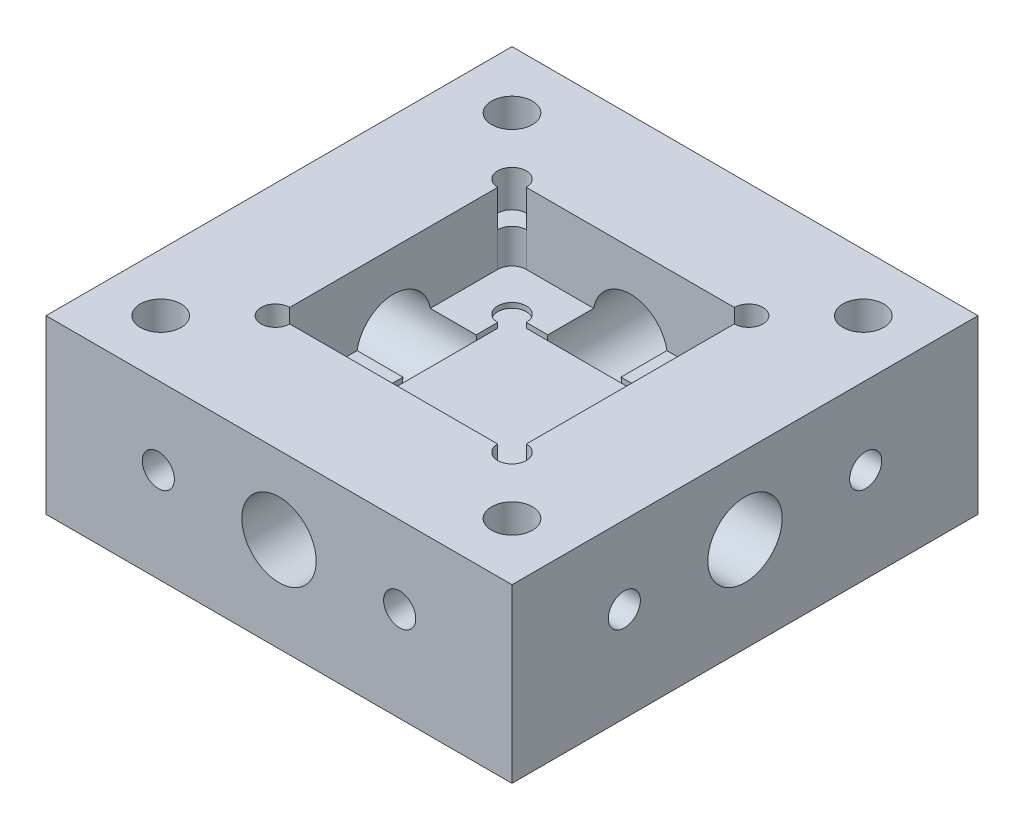
SolidWorks part; units mm, degrees
ref_plane "Front Plane" through (0, 0, 0) normal (0, 0, 1) x (1, 0, 0)
ref_plane "Top Plane" through (0, 0, 0) normal (0, 1, 0) x (1, 0, 0)
ref_plane "Right Plane" through (0, 0, 0) normal (1, 0, 0) x (0, 0, -1)
sketch "Sketch1" plane through (0, 0, 0) normal (0, 1, 0) x (1, 0, 0)
  line L1 (-12.9, -12.9) -> (12.9, -12.9)
  line L2 (-12.9, -12.9) -> (-12.9, 12.9)
  line L3 (-12.9, 12.9) -> (12.9, 12.9)
  line L4 (12.9, -12.9) -> (12.9, 12.9)
  line L5 (-12.9, -12.9) -> (12.9, 12.9) construction
  line L6 (-12.9, 12.9) -> (12.9, -12.9) construction
  point P0 (0, 0)
  dimension "D1" = 25.8
  dimension "D2" = 25.8
extrude "Boss-Extrude1" add sketch "Sketch1" along normal blind 9.525
sketch "Sketch3" plane through (-12.9, 0, 0) normal (-1, 0, 0) x (0, 0, 1)
  circle A0 centre (0, 5.2324) radius 2.0574
  dimension "D1" = 4.1148
extrude "Cut-Extrude3" cut sketch "Sketch3" against normal blind 8.89
mirror "Mirror1" about plane through (0, 0, 0) normal (1, 0, 0) of "Cut-Extrude3"
sketch "Sketch7" plane through (0, 0, -12.9) normal (0, 0, -1) x (-1, 0, 0)
  circle A0 centre (0, 5.2324) radius 2.0574
  dimension "D1" = 4.1148
extrude "Cut-Extrude5" cut sketch "Sketch7" against normal blind 8.89
mirror "Mirror2" about plane through (0, 0, 0) normal (0, 0, 1) of "Cut-Extrude5"
sketch "Sketch8" plane through (12.9, 0, 0) normal (1, 0, 0) x (0, 0, -1)
  point P3 (6.6802, 5.2324)
sketch "Sketch12" plane through (0, 9.525, 0) normal (0, 1, 0) x (1, 0, 0)
  line L10 (9.725, -9.725) -> (9.725, 9.725)
  line L11 (9.725, 9.725) -> (-9.725, 9.725)
  line L12 (-9.725, 9.725) -> (-9.725, -9.725)
  line L14 (-9.725, -9.725) -> (9.725, -9.725)
  line L15 (9.725, -9.725) -> (9.725, 9.725)
  line L16 (9.725, 9.725) -> (-9.725, 9.725)
  line L17 (-9.725, 9.725) -> (-9.725, -9.725)
  line L18 (-9.725, -9.725) -> (9.725, -9.725)
  dimension "D1" = 3.175
sketch "Sketch14" plane through (0, 9.525, 0) normal (0, 1, 0) x (1, 0, 0)
  line L1 (-5.7562, -6.55) -> (5.7562, -6.55)
  line L2 (-6.55, -5.7562) -> (-6.55, 5.7562)
  line L3 (-5.7562, 6.55) -> (5.7562, 6.55)
  line L4 (6.55, -5.7562) -> (6.55, 5.7562)
  line L5 (-6.55, -6.55) -> (6.55, 6.55) construction
  line L6 (-6.55, 6.55) -> (6.55, -6.55) construction
  arc A0 (5.7562, -6.55) -> (6.55, -5.7562) centre (5.7562, -5.7562) ccw
  arc A1 (-6.55, -5.7562) -> (-5.7562, -6.55) centre (-5.7562, -5.7562) ccw
  arc A2 (6.55, 5.7562) -> (5.7562, 6.55) centre (5.7562, 5.7562) ccw
  arc A3 (-6.55, 5.7562) -> (-5.7562, 6.55) centre (-5.7562, 5.7562) cw
  point P0 (0, 0)
  dimension "D3" = 0.7937
  dimension "D1" = 13.1
  dimension "D2" = 13.1
extrude "Cut-Extrude10" cut sketch "Sketch14" against normal blind 3.9376
sketch "Sketch15" plane through (0, 5.5874, 0) normal (0, 1, 0) x (1, 0, 0)
  line L1 (-3.2162, -4.01) -> (3.2162, -4.01)
  line L2 (-4.01, -3.2162) -> (-4.01, 3.2162)
  line L3 (-3.2163, 4.01) -> (3.2162, 4.01)
  line L4 (4.01, -3.2162) -> (4.01, 3.2163)
  line L5 (-4.01, -4.01) -> (4.01, 4.01) construction
  line L6 (-4.01, 4.01) -> (4.01, -4.01) construction
  arc A0 (-3.2163, 4.01) -> (-4.01, 3.2162) centre (-4.01, 4.01) ccw
  arc A1 (4.01, 3.2163) -> (3.2162, 4.01) centre (4.01, 4.01) ccw
  arc A2 (3.2162, -4.01) -> (4.01, -3.2162) centre (4.01, -4.01) ccw
  arc A3 (-4.01, -3.2162) -> (-3.2162, -4.01) centre (-4.01, -4.01) ccw
  point P0 (0, 0)
  point P16 (0, 0)
  dimension "D3" = 4
  dimension "D1" = 8.02
  dimension "D2" = 8.02
extrude "Cut-Extrude11" cut sketch "Sketch15" against normal blind 0.28
sketch "Sketch16" plane through (0, 0, -12.9) normal (0, 0, -1) x (-1, 0, 0)
  point P3 (6.6802, 5.2324)
hole_wizard "#4-40 Tapped Hole2" positions "Sketch18" profile "Sketch19" tap size "#4-40" standard "ANSI Inch" end condition through all
sketch "Sketch18" plane through (0, 9.525, 0) normal (0, 1, 0) x (1, 0, 0)
  point P0 (9.725, -9.725)
  point P3 (-9.725, -9.725)
  point P6 (-9.725, 9.725)
  point P9 (9.725, 9.725)
sketch "Sketch19" plane through (9.725, 9.525, 9.725) normal (1, 0, 0) x (0, 0, 1)
  line L0 (0, 0) -> (0, 9.525)
  line L1 (0, 9.525) -> (1.1303, 9.525)
  line L2 (1.1303, 9.525) -> (1.1303, 0)
  line L5 (1.1303, 0) -> (0, 0)
  line L11 (0, -6.35) -> (0, 107.95) construction
  dimension "Thru Tap Drill Dia." = 2.2606
  dimension "Thru Tap Drill Depth" = 9.525
cosmetic thread "Hole Thread13" parameters "D2"=2.8448
cosmetic thread "Hole Thread14" parameters "D2"=2.8448
cosmetic thread "Hole Thread15" parameters "D2"=2.8448
cosmetic thread "Hole Thread16" parameters "D2"=2.8448
hole_wizard "#2-56 Tapped Hole1" positions "Sketch20" profile "Sketch22" tap size "#2-56" standard "ANSI Inch"
sketch "Sketch20" plane through (0, 0, -12.9) normal (0, 0, -1) x (-1, 0, 0)
  point P0 (6.6802, 5.2324)
sketch "Sketch22" plane through (-6.6802, 5.2324, -12.9) normal (1, 0, 0) x (0, 1, 0)
  line L0 (0, 0) -> (0, 5.3602)
  line L1 (0, 5.3602) -> (0.889, 4.826)
  line L2 (0.889, 4.826) -> (0.889, 0)
  line L5 (0.889, 0) -> (0, 0)
  line L10 (0, 5.3602) -> (-0.889, 4.826) construction
  line L11 (0, -6.35) -> (0, 107.95) construction
  dimension "Tap Drill Dia." = 1.778
  dimension "Tap Drill Depth" = 4.826
  dimension "Drill Angle" = 118
cosmetic thread "Hole Thread17" parameters "D1"=1.778, "D2"=2.1844
mirror "Mirror7" about plane through (0, 0, 0) normal (1, 0, 0) of "#2-56 Tapped Hole1"
mirror "Mirror8" about plane through (0, 0, 0) normal (0, 0, 1) of "Mirror7", "#2-56 Tapped Hole1"
hole_wizard "#2-56 Tapped Hole2" positions "Sketch23" profile "Sketch24" tap size "#2-56" standard "ANSI Inch"
sketch "Sketch23" plane through (12.9, 0, 0) normal (1, 0, 0) x (0, 0, -1)
  point P0 (6.6802, 5.2324)
sketch "Sketch24" plane through (12.9, 5.2324, -6.6802) normal (0, 1, 0) x (0, 0, -1)
  line L0 (0, 0) -> (0, 5.3602)
  line L1 (0, 5.3602) -> (0.889, 4.826)
  line L2 (0.889, 4.826) -> (0.889, 0)
  line L5 (0.889, 0) -> (0, 0)
  line L10 (0, 5.3602) -> (-0.889, 4.826) construction
  line L11 (0, -6.35) -> (0, 107.95) construction
  dimension "Tap Drill Dia." = 1.778
  dimension "Tap Drill Depth" = 4.826
  dimension "Drill Angle" = 118
cosmetic thread "Hole Thread18" parameters "D1"=1.778, "D2"=2.1844
mirror "Mirror9" about plane through (0, 0, 0) normal (0, 0, 1) of "#2-56 Tapped Hole2"
mirror "Mirror10" about plane through (0, 0, 0) normal (1, 0, 0) of "Mirror9", "#2-56 Tapped Hole2"
sketch "Sketch25" plane through (0, 9.525, 0) normal (0, 1, 0) x (1, 0, 0)
  line L5 (-6.55, -6.55) -> (6.55, 6.55) construction
  line L6 (-6.55, 6.55) -> (6.55, -6.55) construction
  circle A0 centre (-6.55, 6.55) radius 0.7938
  circle A1 centre (6.55, 6.55) radius 0.7938
  circle A2 centre (6.55, -6.55) radius 0.7938
  circle A3 centre (-6.55, -6.55) radius 0.7938
  point P0 (0, 0)
  point P16 (0, 0)
  dimension "D3" = 4
  dimension "D1" = 13.1
  dimension "D2" = 13.1
extrude "Cut-Extrude12" cut sketch "Sketch25" against normal blind 2.032
